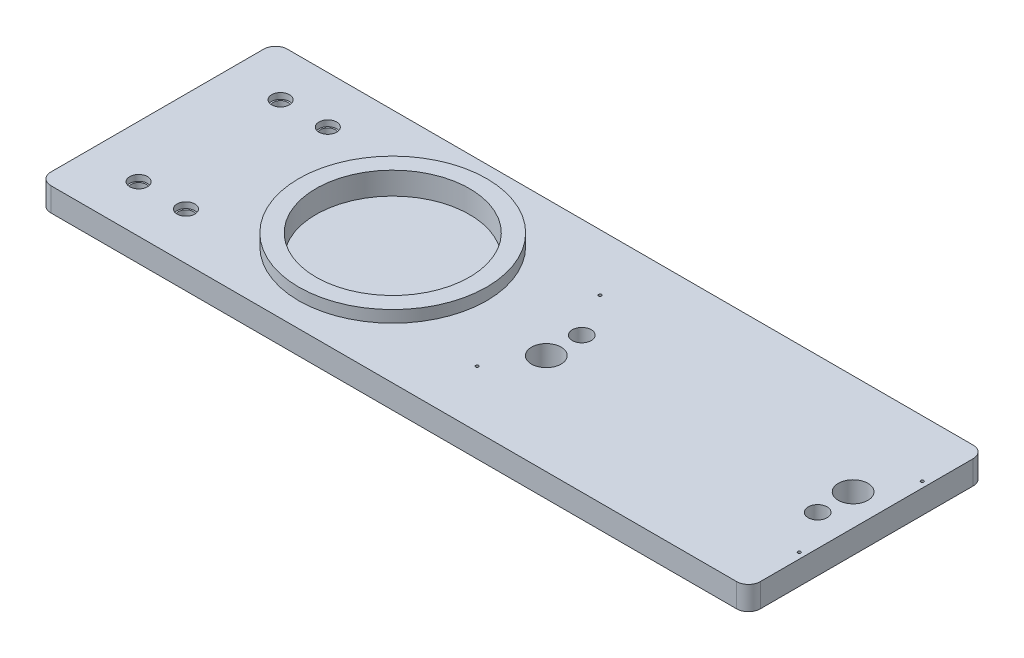
SolidWorks part; units mm, degrees
ref_plane "Front Plane" through (0, 0, 0) normal (0, 0, 1) x (1, 0, 0)
ref_plane "Top Plane" through (0, 0, 0) normal (0, 1, 0) x (1, 0, 0)
ref_plane "Right Plane" through (0, 0, 0) normal (1, 0, 0) x (0, 0, -1)
sketch "Sketch1" plane through (0, 0, 0) normal (0, 1, 0) x (1, 0, 0)
  line L1 (0, 0) -> (-600, 0)
  line L2 (0, 0) -> (0, 200)
  line L3 (0, 200) -> (-600, 200)
  line L4 (-600, 0) -> (-600, 200)
  dimension "D1" = 600
extrude "Boss-Extrude1" add sketch "Sketch1" along normal blind 20
sketch "Sketch2" plane through (0, 20, 0) normal (0, 1, 0) x (1, 0, 0)
  line L0 (0, 200) -> (-600, 200) construction
  line L1 (-600, 200) -> (-600, 0) construction
  line L2 (-600, 0) -> (0, 0) construction
  circle A0 centre (-555.774, 160) radius 6.25
  circle A1 centre (-555.774, 40) radius 6.25
  circle A2 centre (-515.774, 40) radius 6.25
  circle A3 centre (-515.774, 160) radius 6.25
  dimension "D1" = 12.5
  dimension "D4" = 12.5
  dimension "D6" = 40
  dimension "D5" = 40
  dimension "D2" = 40
  dimension "D3" = 200
  dimension "D7" = 40
  dimension "D8" = 40
  dimension "D9" = 40
  dimension "D10" = 44.226
  dimension "D11" = 44.226
extrude "Cut-Extrude1" cut sketch "Sketch2" against normal through all
sketch "Sketch4" plane through (0, 20, 0) normal (0, 1, 0) x (1, 0, 0)
  circle A0 centre (-555.774, 160) radius 7.5
  circle A1 centre (-555.774, 40) radius 7.5
  circle A2 centre (-515.774, 40) radius 7.5
  circle A3 centre (-515.774, 160) radius 7.5
  dimension "D1" = 15
  dimension "D2" = 15
  dimension "D3" = 40
  dimension "D4" = 40
extrude "Cut-Extrude2" cut sketch "Sketch4" against normal blind 5
ref_plane "Plane1" through (0, 30, 0) normal (0, 1, 0) x (1, 0, 0)
sketch "Sketch5" plane through (0, 20, 0) normal (0, 1, 0) x (1, 0, 0)
  line L0 (-282.5, 200) -> (-282.5, 0) construction
  line L1 (0, 200) -> (-600, 200) construction
  line L2 (-600, 0) -> (0, 0) construction
  line L3 (0, 0) -> (0, 200) construction
  line L4 (-282.5, 157) -> (0, 157) construction
  line L5 (-282.5, 43) -> (0, 43) construction
  line L6 (-282.5, 53) -> (-272.5, 53) construction
  line L7 (-272.5, 53) -> (-272.5, 43) construction
  line L8 (-277.5, 53) -> (-277.5, 43) construction
  line L9 (-282.5, 100) -> (0, 100) construction
  line L10 (-141.25, 157) -> (-141.25, 43) construction
  circle A0 centre (-277.5, 48) radius 1.25
  circle A1 centre (-277.5, 152) radius 1.25
  circle A2 centre (-5, 48) radius 1.25
  circle A3 centre (-5, 152) radius 1.25
  dimension "D7" = 2.5
  dimension "D1" = 282.5
  dimension "D2" = 200
  dimension "D3" = 43
  dimension "D4" = 43
  dimension "D5" = 10
  dimension "D6" = 10
extrude "Cut-Extrude3" cut sketch "Sketch5" against normal through all
fillet "Fillet1" radius 10 4 edges at (0, 10, 0) (0, 10, -200) (-600, 10, 0) (-600, 10, -200)
sketch "Sketch6" plane through (0, 20, 0) normal (0, 1, 0) x (1, 0, 0)
  line L2 (-400.8671, 200) -> (-400.8671, 0) construction
  line L3 (-10, 200) -> (-590, 200) construction
  line L4 (-590, 0) -> (-10, 0) construction
  circle A0 centre (-400.8671, 100) radius 79.4916
extrude "Boss-Extrude2" add sketch "Sketch6" along normal blind 10
sketch "Sketch7" plane through (0, 30, 0) normal (0, 1, 0) x (1, 0, 0)
  line L0 (-400.8671, 179.4916) -> (-400.8671, 20.5084) construction
  circle A0 centre (-400.8671, 100) radius 79.4916 construction
  circle A1 centre (-400.8671, 100) radius 79.4916 construction
  circle A2 centre (-400.8671, 100) radius 64.9366
extrude "Cut-Extrude4" cut sketch "Sketch7" against normal blind 19
sketch "Sketch8" plane through (0, 20, 0) normal (0, 1, 0) x (1, 0, 0)
  line L0 (-5, 152) -> (-5, 157) construction
  line L2 (-5, 152) -> (0, 152) construction
  line L3 (0, 157) -> (-26.5, 157) construction
  line L4 (-277.5, 152) -> (-277.5, 157) construction
  line L5 (-26.5, 200) -> (-26.5, 0) construction
  line L6 (-10, 200) -> (-590, 200) construction
  line L7 (-590, 0) -> (-10, 0) construction
  line L8 (0, 10) -> (0, 190) construction
  line L9 (-277.5, 157) -> (-272.5, 157) construction
  circle A0 centre (-26.5, 115) radius 12.5
  circle A1 centre (-26.5, 85) radius 8
  circle A2 centre (-256, 115) radius 8
  circle A3 centre (-256, 85) radius 12.5
  dimension "D4" = 25
  dimension "D6" = 16
  dimension "D11" = 30
  dimension "D12" = 16
  dimension "D13" = 25
  dimension "D1" = 5
  dimension "D2" = 42
  dimension "D3" = 5
  dimension "D5" = 30
  dimension "D7" = 5
  dimension "D8" = 5
  dimension "D9" = 21.5
extrude "Cut-Extrude5" cut sketch "Sketch8" against normal through all
